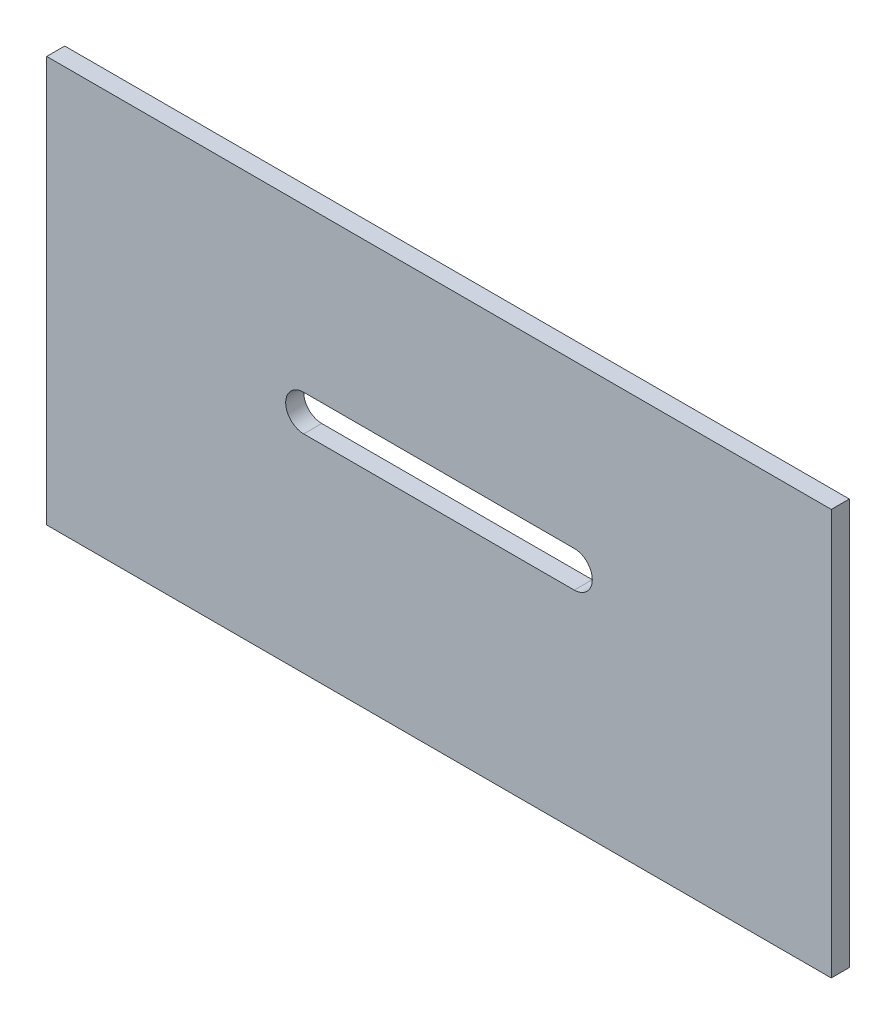
SolidWorks part; units mm, degrees
ref_plane "Front Plane" through (0, 0, 0) normal (0, 0, 1) x (1, 0, 0)
ref_plane "Top Plane" through (0, 0, 0) normal (0, 1, 0) x (1, 0, 0)
ref_plane "Right Plane" through (0, 0, 0) normal (1, 0, 0) x (0, 0, -1)
sketch "Sketch1" plane through (0, 0, 0) normal (0, 0, 1) x (1, 0, 0)
  line L1 (-43.5, 22.5) -> (43.5, 22.5)
  line L2 (-43.5, 22.5) -> (-43.5, -22.5)
  line L3 (-43.5, -22.5) -> (43.5, -22.5)
  line L4 (43.5, 22.5) -> (43.5, -22.5)
  line L5 (-43.5, 22.5) -> (43.5, -22.5) construction
  line L6 (-43.5, -22.5) -> (43.5, 22.5) construction
  point P0 (0, 0)
  dimension "D1" = 87
  dimension "D2" = 45
extrude "Boss-Extrude1" add sketch "Sketch1" along normal blind 2
sketch "Sketch2" plane through (0, 0, 2) normal (0, 0, 1) x (1, 0, 0)
  line L0 (-15, 2.5) -> (15, 2.5) construction
  line L1 (-15, 4.5) -> (15, 4.5)
  line L2 (-15, 0.5) -> (15, 0.5)
  line L3 (43.5, -22.5) -> (43.5, 22.5) construction
  line L4 (-43.5, -22.5) -> (43.5, -22.5) construction
  arc A0 (-15, 4.5) -> (-15, 0.5) centre (-15, 2.5) ccw
  arc A1 (15, 0.5) -> (15, 4.5) centre (15, 2.5) ccw
  point P2 (0, 2.5)
  dimension "D1" = 2
  dimension "D2" = 30
  dimension "D3" = 43.5
  dimension "D4" = 25
extrude "Cut-Extrude1" cut sketch "Sketch2" against normal blind 2
